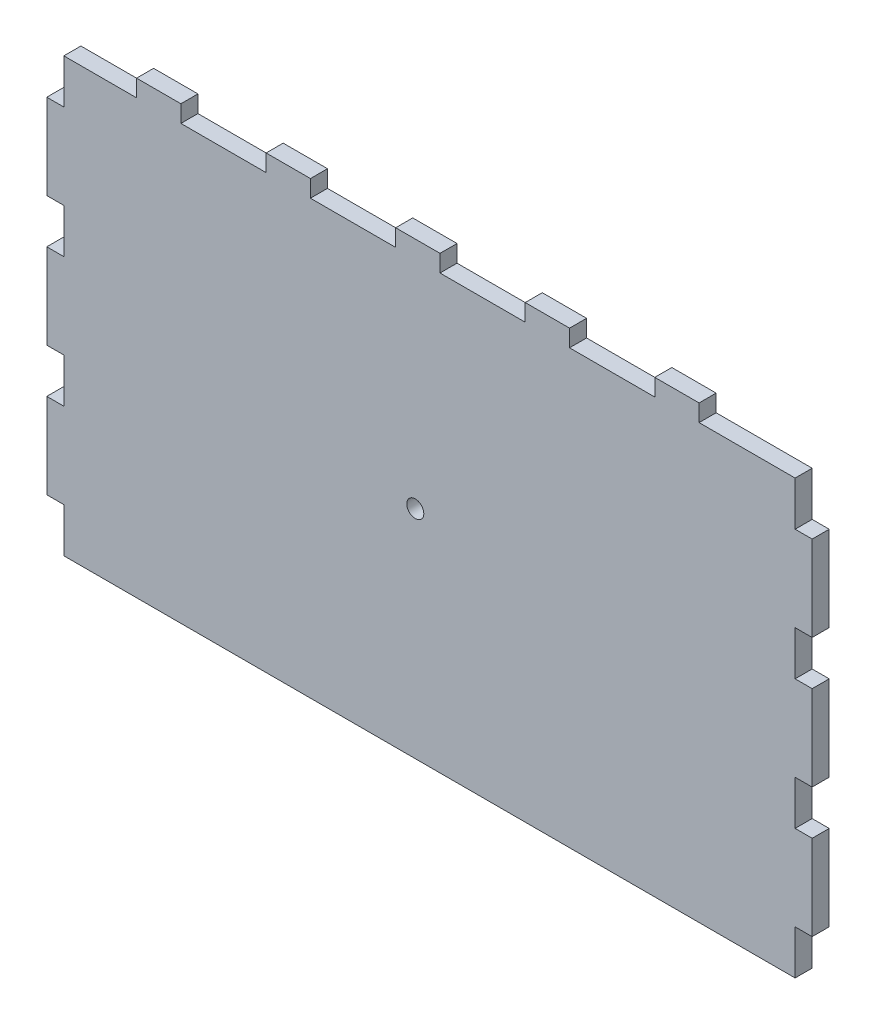
SolidWorks part; units mm, degrees
material "ENPH 253 Hardboard"
ref_plane "Front Plane" through (0, 0, 0) normal (0, 0, 1) x (1, 0, 0)
ref_plane "Top Plane" through (0, 0, 0) normal (0, 1, 0) x (1, 0, 0)
ref_plane "Right Plane" through (0, 0, 0) normal (1, 0, 0) x (0, 0, -1)
sketch "Sketch1" plane through (0, 0, 0) normal (0, 0, 1) x (1, 0, 0)
  line L1 (-67.35, 38.1) -> (67.35, 38.1)
  line L2 (-67.35, 38.1) -> (-67.35, -38.1)
  line L3 (-67.35, -38.1) -> (67.35, -38.1)
  line L4 (67.35, 38.1) -> (67.35, -38.1)
  line L5 (-67.35, 38.1) -> (67.35, -38.1) construction
  line L6 (-67.35, -38.1) -> (67.35, 38.1) construction
  point P0 (0, 0)
  dimension "D1" = 134.7
  dimension "D2" = 76.2
extrude "Boss-Extrude1" add sketch "Sketch1" along normal blind 3
sketch "Sketch2" plane through (0, 0, 3) normal (0, 0, 1) x (1, 0, 0)
  line L1 (-67.35, 38.1) -> (-64.35, 38.1)
  line L2 (-67.35, 38.1) -> (-67.35, 30.3)
  line L3 (-67.35, 30.3) -> (-64.35, 30.3)
  line L4 (-64.35, 38.1) -> (-64.35, 30.3)
  dimension "D1" = 3
  dimension "D2" = 7.8
extrude "Cut-Extrude1" cut sketch "Sketch2" against normal through all
pattern_linear "LPattern1" count 4 spacing 22.8 along (0, -1, 0) of "Cut-Extrude1"
hole_wizard "Ø3.0mm Clearance Dowel Hole1" positions "Sketch3" profile "Sketch4" hole size "Ø3.0" standard "ANSI Metric" end condition through all
sketch "Sketch3" plane through (0, 0, 3) normal (0, 0, 1) x (1, 0, 0)
  line L0 (-67.35, 7.5) -> (-67.35, -7.5) construction
  point P0 (-2.5, 0)
  dimension "D1" = 64.85
sketch "Sketch4" plane through (-2.5, 0, 3) normal (1, 0, 0) x (0, -1, 0)
  line L0 (0, 0) -> (0, 3)
  line L1 (0, 3) -> (1.5, 3)
  line L2 (1.5, 3) -> (1.5, 0)
  line L5 (1.5, 0) -> (0, 0)
  line L11 (0, -6.35) -> (0, 107.95) construction
  dimension "Thru Hole Dia." = 3
  dimension "Thru Hole Depth" = 3
mirror "Mirror4" about plane through (0, 0, 0) normal (1, 0, 0) of "LPattern1", "Cut-Extrude1"
sketch "Sketch5" plane through (0, 38.1, 0) normal (0, 1, 0) x (1, 0, 0)
  line L0 (64.35, 0) -> (-64.35, 0) construction
  line L1 (-43.75, 0) -> (-51.55, 0)
  line L2 (-43.75, 0) -> (-43.75, -3)
  line L3 (-43.75, -3) -> (-51.55, -3)
  line L4 (-51.55, 0) -> (-51.55, -3)
  line L5 (64.35, -3) -> (-64.35, -3) construction
  line L6 (-64.35, 0) -> (-64.35, -3) construction
  point P10 (-51.55, -1.5)
  dimension "D1" = 12.8
  dimension "D2" = 7.8
extrude "Boss-Extrude2" add sketch "Sketch5" along normal blind 3
pattern_linear "LPattern2" count 5 spacing 22.8 along (1, 0, 0) of "Boss-Extrude2"
